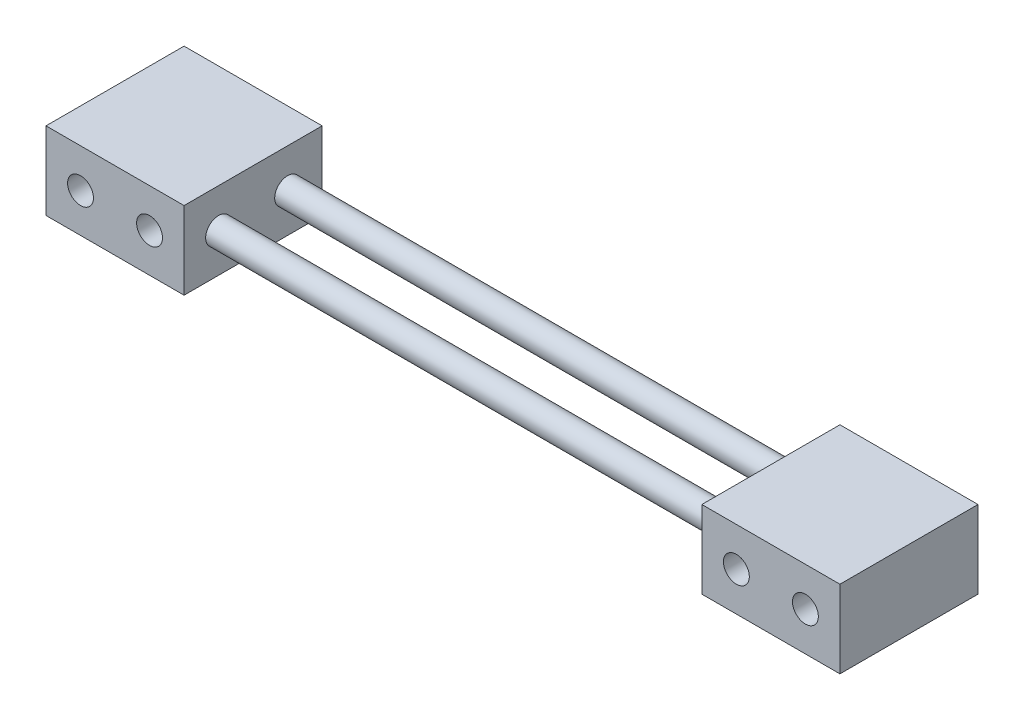
SolidWorks part; units mm, degrees
ref_plane "Front Plane" through (0, 0, 0) normal (0, 0, 1) x (1, 0, 0)
ref_plane "Top Plane" through (0, 0, 0) normal (0, 1, 0) x (1, 0, 0)
ref_plane "Right Plane" through (0, 0, 0) normal (1, 0, 0) x (0, 0, -1)
sketch "Sketch1" plane through (0, 0, 0) normal (0, 1, 0) x (1, 0, 0)
  line L1 (0, 0) -> (-80, 0)
  line L2 (0, 0) -> (0, 80)
  line L3 (0, 80) -> (-80, 80)
  line L4 (-80, 0) -> (-80, 80)
  dimension "D1" = 80
  dimension "D2" = 80
extrude "Boss-Extrude1" add sketch "Sketch1" along normal blind 45
sketch "Sketch2" plane through (0, 0, 0) normal (0, 0, 1) x (1, 0, 0)
  line L0 (-80, 45) -> (-80, 0) construction
  line L1 (0, 45) -> (0, 0) construction
  line L2 (-80, 45) -> (0, 45) construction
  line L3 (-80, 0) -> (0, 0) construction
  circle A0 centre (-60, 22.5) radius 7.5
  circle A1 centre (-20, 22.5) radius 7.5
  point P8 (0, 22.5)
  dimension "D1" = 15
  dimension "D2" = 15
  dimension "D3" = 20
  dimension "D4" = 20
  dimension "D5" = 22.5
  dimension "D6" = 22.5
extrude "Cut-Extrude1" cut sketch "Sketch2" against normal through all
sketch "Sketch3" plane through (0, 0, 0) normal (1, 0, 0) x (0, 0, -1)
  line L0 (0, 45) -> (80, 45) construction
  line L1 (0, 45) -> (0, 0) construction
  line L2 (80, 45) -> (80, 0) construction
  circle A0 centre (20, 22.5) radius 7.5
  circle A1 centre (60, 22.5) radius 7.5
  dimension "D1" = 15
  dimension "D2" = 15
  dimension "D3" = 22.5
  dimension "D4" = 22.5
  dimension "D5" = 20
  dimension "D6" = 20
ref_plane "Plane1" through (150, 0, 0) normal (1, 0, 0) x (0, 0, -1)
extrude "Boss-Extrude2" add sketch "Sketch3" along normal blind 300
mirror "Mirror3" about plane through (150, 0, 0) normal (1, 0, 0) of "Cut-Extrude1", "Boss-Extrude1"
